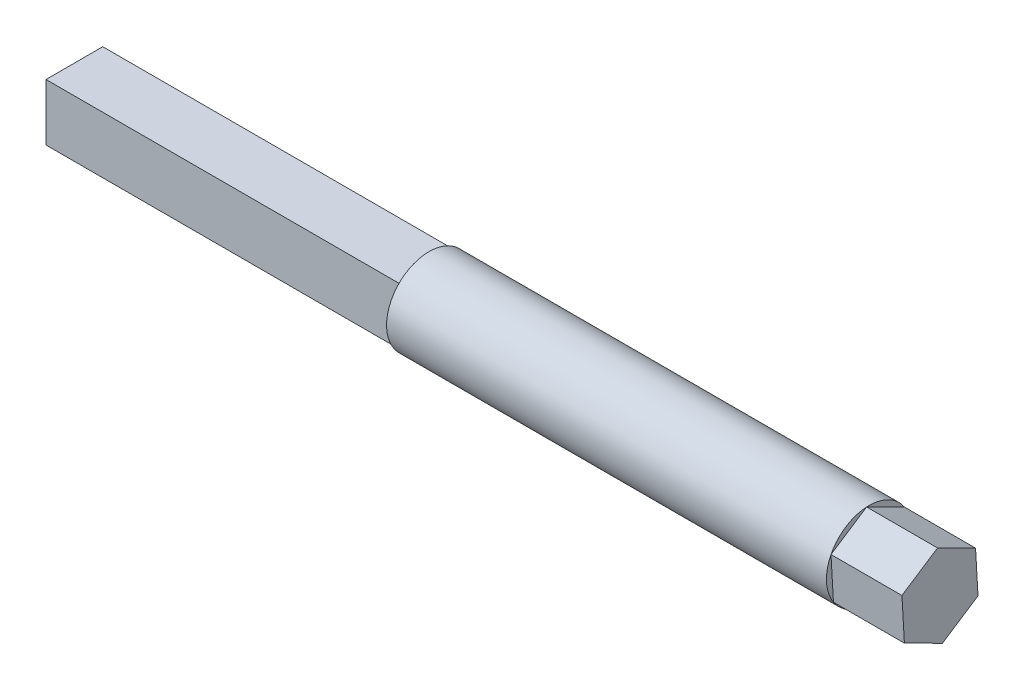
SolidWorks part; units mm, degrees
material "AISI 1020"
ref_plane "Front Plane" through (0, 0, 0) normal (0, 0, 1) x (1, 0, 0)
ref_plane "Top Plane" through (0, 0, 0) normal (0, 1, 0) x (1, 0, 0)
ref_plane "Right Plane" through (0, 0, 0) normal (1, 0, 0) x (0, 0, -1)
sketch "Sketch1" plane through (0, 0, 0) normal (1, 0, 0) x (0, 0, -1)
  line L1 (-1, -1) -> (1, -1)
  line L2 (-1, -1) -> (-1, 1)
  line L3 (-1, 1) -> (1, 1)
  line L4 (1, -1) -> (1, 1)
  line L5 (-1, -1) -> (1, 1) construction
  line L6 (-1, 1) -> (1, -1) construction
  point P0 (0, 0)
  dimension "D1" = 2
  dimension "D2" = 2
ref_plane "Plane1" through (70, 0, 0) normal (1, 0, 0) x (0, 0, -1)
sketch "Sketch12" plane through (70, 0, 0) normal (1, 0, 0) x (0, 0, -1)
  line L0 (-0.0526, 0.2) -> (0.0474, 0.2)
  line L1 (0.0474, 0.2) -> (0.0474, 0.0632)
  line L2 (0.0474, 0.0632) -> (0.2, 0.0632)
  line L3 (0.2, 0.0632) -> (0.2, -0.0368)
  line L4 (0.2, -0.0368) -> (0.0526, -0.0368)
  line L5 (0.0526, -0.0368) -> (0.0526, -0.2)
  line L6 (0.0526, -0.2) -> (-0.0474, -0.2)
  line L7 (-0.0474, -0.2) -> (-0.0474, -0.0368)
  line L8 (-0.0474, -0.0368) -> (-0.2, -0.0368)
  line L9 (-0.2, -0.0368) -> (-0.2, 0.0632)
  line L10 (-0.2, 0.0632) -> (-0.0526, 0.0632)
  line L11 (-0.0526, 0.0632) -> (-0.0526, 0.2)
  line L12 (0, 0) -> (50000, 0) construction
  line L13 (0, -1000) -> (0, 49000) construction
  dimension "D1" = 0.1
  dimension "D2" = 0.1
  dimension "D3" = 0.1
  dimension "D4" = 0.1
  dimension "D5" = 0.2
  dimension "D6" = 0.4
  dimension "D7" = 0.2
  dimension "D8" = 0.2
  dimension "D9" = 0.2
ref_plane "Plane2" through (30, 0, 0) normal (1, 0, 0) x (0, 0, -1)
sketch "Sketch2" plane through (30, 0, 0) normal (1, 0, 0) x (0, 0, -1)
  line L1 (-1, -1) -> (1, -1)
  line L2 (-1, -1) -> (-1, 1)
  line L3 (-1, 1) -> (1, 1)
  line L4 (1, -1) -> (1, 1)
  line L5 (-1, -1) -> (1, 1) construction
  line L6 (-1, 1) -> (1, -1) construction
  point P0 (0, 0)
loft "Loft1" add profiles "Sketch1", "Sketch2"
sketch "Sketch3" plane through (30, 0, 0) normal (1, 0, 0) x (0, 0, -1)
  circle A0 centre (0, 0) radius 3
  dimension "D1" = 6
ref_plane "Plane3" through (64, 0, 0) normal (1, 0, 0) x (0, 0, -1)
sketch "Sketch4" plane through (64, 0, 0) normal (1, 0, 0) x (0, 0, -1)
  circle A0 centre (0, 0) radius 3
extrude "Boss-Extrude1" add sketch "Sketch3" along normal blind 31 contours A0
sketch "Sketch6" plane through (70, 0, 0) normal (1, 0, 0) x (0, 0, -1)
  line L0 (-0.5, 0.5) -> (-0.5, 2)
  line L1 (-0.5, 2) -> (0.5, 2)
  line L2 (0.5, 2) -> (0.5, 0.5)
  line L3 (0.5, 0.5) -> (2, 0.5)
  line L4 (2, 0.5) -> (2, -0.5)
  line L5 (2, -0.5) -> (0.5, -0.5)
  line L6 (0.5, -0.5) -> (0.5, -2)
  line L7 (0.5, -2) -> (-0.5, -2)
  line L8 (-0.5, -2) -> (-0.5, -0.5)
  line L9 (-0.5, -0.5) -> (-2, -0.5)
  line L10 (-2, -0.5) -> (-2, 0.5)
  line L11 (-2, 0.5) -> (-0.5, 0.5)
  line L12 (-7.5281, 0) -> (7.5281, 0) construction
  line L13 (0, 4.9607) -> (0, -4.9607) construction
  point P16 (0, 0)
  point P20 (0, 0)
  dimension "D1" = 1
  dimension "D2" = 1
  dimension "D3" = 1
  dimension "D4" = 1
  dimension "D5" = 0.5
  dimension "D6" = 0.5
  dimension "D7" = 0.5
  dimension "D8" = 0.5
  dimension "D9" = 2
  dimension "D10" = 4
  dimension "D11" = 4
  dimension "D12" = 2
ref_plane "Plane4" through (67, 0, 0) normal (1, 0, 0) x (0, 0, -1)
sketch "Sketch7" plane through (67, 0, 0) normal (1, 0, 0) x (0, 0, -1)
  line L0 (-0.5, 0.5258) -> (-0.5, 1.9992)
  line L1 (-0.5, 1.9992) -> (0.5, 1.9992)
  line L2 (0.5, 1.9992) -> (0.5, 0.5)
  line L3 (0.5, 0.5) -> (2, 0.5)
  line L4 (2, 0.5) -> (2, -0.5)
  line L5 (2, -0.5) -> (0.5798, -0.5)
  line L6 (0.5798, -0.5) -> (0.5798, -2)
  line L7 (0.5798, -2) -> (-0.4202, -2)
  line L8 (-0.4202, -2) -> (-0.4202, -0.4742)
  line L9 (-0.4202, -0.4742) -> (-2, -0.4742)
  line L10 (-2, -0.4742) -> (-2, 0.5258)
  line L11 (-2, 0.5258) -> (-0.5, 0.5258)
  line L12 (-3.5898, 0) -> (3.5898, 0) construction
  line L14 (0, -4.095) -> (0, 4.095) construction
  line L15 (0, 1.9957) -> (0, -1.9957) construction
  point P14 (0.1945, 0.0315)
  point P16 (0, 0)
  point P17 (0.1945, 0.0315)
  point P24 (0, 0)
  point P28 (0, 0)
  dimension "D1" = 0.5
  dimension "D2" = 0.5
  dimension "D3" = 0.5
  dimension "D4" = 0.5
  dimension "D5" = 4
  dimension "D6" = 4
  dimension "D7" = 2
  dimension "D8" = 2
  dimension "D9" = 2
  dimension "D10" = 1.9992
sketch "Sketch14" plane through (61, 0, 0) normal (1, 0, 0) x (0, 0, -1)
  circle A1 centre (0, 0) radius 3
  circle A2 centre (0, 0) radius 3
  dimension "D1" = 0
sketch "Sketch17" plane through (61, 0, 0) normal (1, 0, 0) x (0, 0, -1)
  line L1 (2.5079, 1.6463) -> (-0.1718, 2.9951)
  line L2 (-0.1718, 2.9951) -> (-2.6797, 1.3487)
  line L3 (-2.6797, 1.3487) -> (-2.5079, -1.6463)
  line L4 (-2.5079, -1.6463) -> (0.1718, -2.9951)
  line L5 (0.1718, -2.9951) -> (2.6797, -1.3487)
  line L6 (2.6797, -1.3487) -> (2.5079, 1.6463)
  circle A0 centre (0, 0) radius 2.5981 construction
  circle A1 centre (0, 0) radius 3 construction
extrude "Boss-Extrude4" add sketch "Sketch17" along normal blind 5
sketch "Sketch18" plane through (0, 0, 0) normal (-1, 0, 0) x (0, 0, 1)
  line L1 (-2, 2) -> (2, 2)
  line L2 (-2, 2) -> (-2, -2)
  line L3 (-2, -2) -> (2, -2)
  line L4 (2, 2) -> (2, -2)
  line L5 (-2, 2) -> (2, -2) construction
  line L6 (-2, -2) -> (2, 2) construction
  point P0 (0, 0)
  dimension "D1" = 4
  dimension "D2" = 4
extrude "Boss-Extrude5" add sketch "Sketch18" against normal blind 30
sketch "Sketch19" plane through (0, 0, 0) normal (-1, 0, 0) x (0, 0, 1)
  point P0 (0, 0)
sketch "Sketch20" plane through (0, 0, 0) normal (-1, 0, 0) x (0, 0, 1)
  point P0 (0, 0)
  point P1 (8.051, 3.518)
sketch "Sketch21" plane through (0, 0, 0) normal (-1, 0, 0) x (0, 0, 1)
  line L1 (-2, -2) -> (2, -2)
  line L2 (-2, -2) -> (-2, 2)
  line L3 (-2, 2) -> (2, 2)
  line L4 (2, -2) -> (2, 2)
  line L5 (-2, -2) -> (2, 2) construction
  line L6 (-2, 2) -> (2, -2) construction
  point P0 (0, 0)
extrude "Cut-Extrude1" cut sketch "Sketch21" against normal blind 5
sketch "Sketch22" plane through (0, 0, 0) normal (0, 1, 0) x (1, 0, 0)
  line L0 (5, -2) -> (5, 2) construction
  line L1 (5, -2) -> (5, 2)
  dimension "D1" = 61
